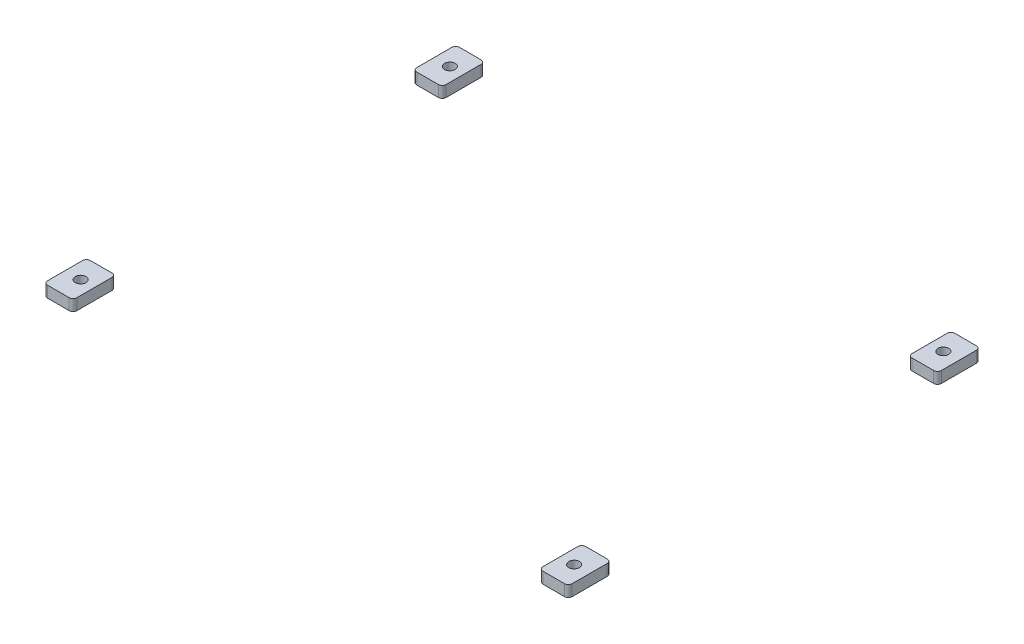
SolidWorks part; units mm, degrees
material "Acrylic (Medium-high impact)"
ref_plane "Front Plane" through (0, 0, 0) normal (0, 0, 1) x (1, 0, 0)
ref_plane "Top Plane" through (0, 0, 0) normal (0, 1, 0) x (1, 0, 0)
ref_plane "Right Plane" through (0, 0, 0) normal (1, 0, 0) x (0, 0, -1)
ref_plane "Plane1" through (0, -2.9, 0) normal (0, 1, 0) x (1, 0, 0)
sketch "Sketch1" plane through (0, -2.9, 0) normal (0, 1, 0) x (1, 0, 0)
  line L0 (121.9, -106) -> (133, -106)
  line L1 (135, -104) -> (135, -86)
  line L2 (133, -84) -> (121.9, -84)
  line L3 (119.9, -86) -> (119.9, -104)
  line L4 (121.9, 84) -> (133, 84)
  line L5 (135, 86) -> (135, 104)
  line L6 (133, 106) -> (121.9, 106)
  line L7 (119.9, 104) -> (119.9, 86)
  line L8 (-133, -106) -> (-121.9, -106)
  line L9 (-119.9, -104) -> (-119.9, -86)
  line L10 (-121.9, -84) -> (-133, -84)
  line L11 (-135, -86) -> (-135, -104)
  line L12 (-133, 84) -> (-121.9, 84)
  line L13 (-119.9, 86) -> (-119.9, 104)
  line L14 (-121.9, 106) -> (-133, 106)
  line L15 (-135, 104) -> (-135, 86)
  arc A0 (119.9, -104) -> (121.9, -106) centre (121.9, -104) ccw
  arc A1 (133, -106) -> (135, -104) centre (133, -104) ccw
  arc A2 (135, -86) -> (133, -84) centre (133, -86) ccw
  arc A3 (121.9, -84) -> (119.9, -86) centre (121.9, -86) ccw
  circle A4 centre (127, -95) radius 2.75
  arc A5 (119.9, 86) -> (121.9, 84) centre (121.9, 86) ccw
  arc A6 (133, 84) -> (135, 86) centre (133, 86) ccw
  arc A7 (135, 104) -> (133, 106) centre (133, 104) ccw
  arc A8 (121.9, 106) -> (119.9, 104) centre (121.9, 104) ccw
  circle A9 centre (127, 95) radius 2.75
  arc A10 (-135, -104) -> (-133, -106) centre (-133, -104) ccw
  arc A11 (-121.9, -106) -> (-119.9, -104) centre (-121.9, -104) ccw
  arc A12 (-119.9, -86) -> (-121.9, -84) centre (-121.9, -86) ccw
  arc A13 (-133, -84) -> (-135, -86) centre (-133, -86) ccw
  circle A14 centre (-127, -95) radius 2.75
  arc A15 (-135, 86) -> (-133, 84) centre (-133, 86) ccw
  arc A16 (-121.9, 84) -> (-119.9, 86) centre (-121.9, 86) ccw
  arc A17 (-119.9, 104) -> (-121.9, 106) centre (-121.9, 104) ccw
  arc A18 (-133, 106) -> (-135, 104) centre (-133, 104) ccw
  circle A19 centre (-127, 95) radius 2.75
extrude "Boss-Extrude1" add sketch "Sketch1" along normal blind 2.9
ref_plane "Plane2" through (0, -5.8, 0) normal (0, 1, 0) x (1, 0, 0)
sketch "Sketch2" plane through (0, -5.8, 0) normal (0, 1, 0) x (1, 0, 0)
  line L0 (121.9, -106) -> (133, -106)
  line L1 (135, -104) -> (135, -86)
  line L2 (133, -84) -> (121.9, -84)
  line L3 (119.9, -86) -> (119.9, -104)
  line L4 (121.9, 84) -> (133, 84)
  line L5 (135, 86) -> (135, 104)
  line L6 (133, 106) -> (121.9, 106)
  line L7 (119.9, 104) -> (119.9, 86)
  line L8 (-133, -106) -> (-121.9, -106)
  line L9 (-119.9, -104) -> (-119.9, -86)
  line L10 (-121.9, -84) -> (-133, -84)
  line L11 (-135, -86) -> (-135, -104)
  line L12 (-133, 84) -> (-121.9, 84)
  line L13 (-119.9, 86) -> (-119.9, 104)
  line L14 (-121.9, 106) -> (-133, 106)
  line L15 (-135, 104) -> (-135, 86)
  arc A0 (119.9, -104) -> (121.9, -106) centre (121.9, -104) ccw
  arc A1 (133, -106) -> (135, -104) centre (133, -104) ccw
  arc A2 (135, -86) -> (133, -84) centre (133, -86) ccw
  arc A3 (121.9, -84) -> (119.9, -86) centre (121.9, -86) ccw
  circle A4 centre (127, -95) radius 2.75
  arc A5 (119.9, 86) -> (121.9, 84) centre (121.9, 86) ccw
  arc A6 (133, 84) -> (135, 86) centre (133, 86) ccw
  arc A7 (135, 104) -> (133, 106) centre (133, 104) ccw
  arc A8 (121.9, 106) -> (119.9, 104) centre (121.9, 104) ccw
  circle A9 centre (127, 95) radius 2.75
  arc A10 (-135, -104) -> (-133, -106) centre (-133, -104) ccw
  arc A11 (-121.9, -106) -> (-119.9, -104) centre (-121.9, -104) ccw
  arc A12 (-119.9, -86) -> (-121.9, -84) centre (-121.9, -86) ccw
  arc A13 (-133, -84) -> (-135, -86) centre (-133, -86) ccw
  circle A14 centre (-127, -95) radius 2.75
  arc A15 (-135, 86) -> (-133, 84) centre (-133, 86) ccw
  arc A16 (-121.9, 84) -> (-119.9, 86) centre (-121.9, 86) ccw
  arc A17 (-119.9, 104) -> (-121.9, 106) centre (-121.9, 104) ccw
  arc A18 (-133, 106) -> (-135, 104) centre (-133, 104) ccw
  circle A19 centre (-127, 95) radius 2.75
extrude "Boss-Extrude2" add sketch "Sketch2" along normal blind 2.9
